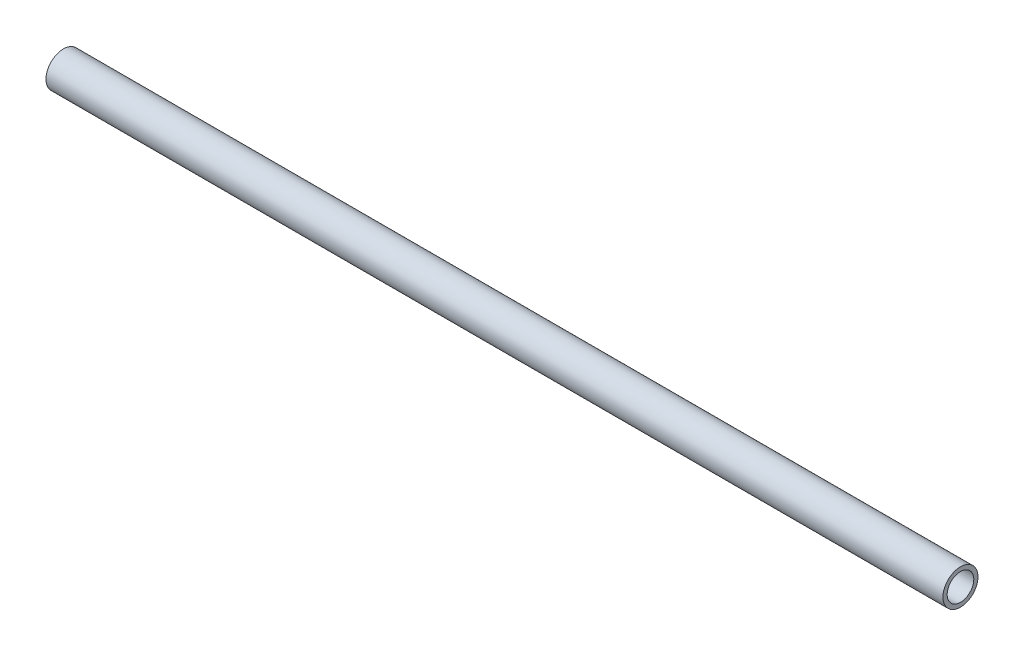
SolidWorks part; units mm, degrees
material "AISI 4130 Steel, annealed at 865C"
ref_plane "Front Plane" through (0, 0, 0) normal (0, 0, 1) x (1, 0, 0)
ref_plane "Top Plane" through (0, 0, 0) normal (0, 1, 0) x (1, 0, 0)
ref_plane "Right Plane" through (0, 0, 0) normal (1, 0, 0) x (0, 0, -1)
sketch "Sketch1" plane through (0, 0, 0) normal (1, 0, 0) x (0, 0, -1)
  circle A0 centre (0, 0) radius 12.7
  circle A1 centre (0, 0) radius 9.652
  dimension "D1" = 25.4
  dimension "D2" = 19.304
extrude "Boss-Extrude1" add sketch "Sketch1" along normal blind 650
